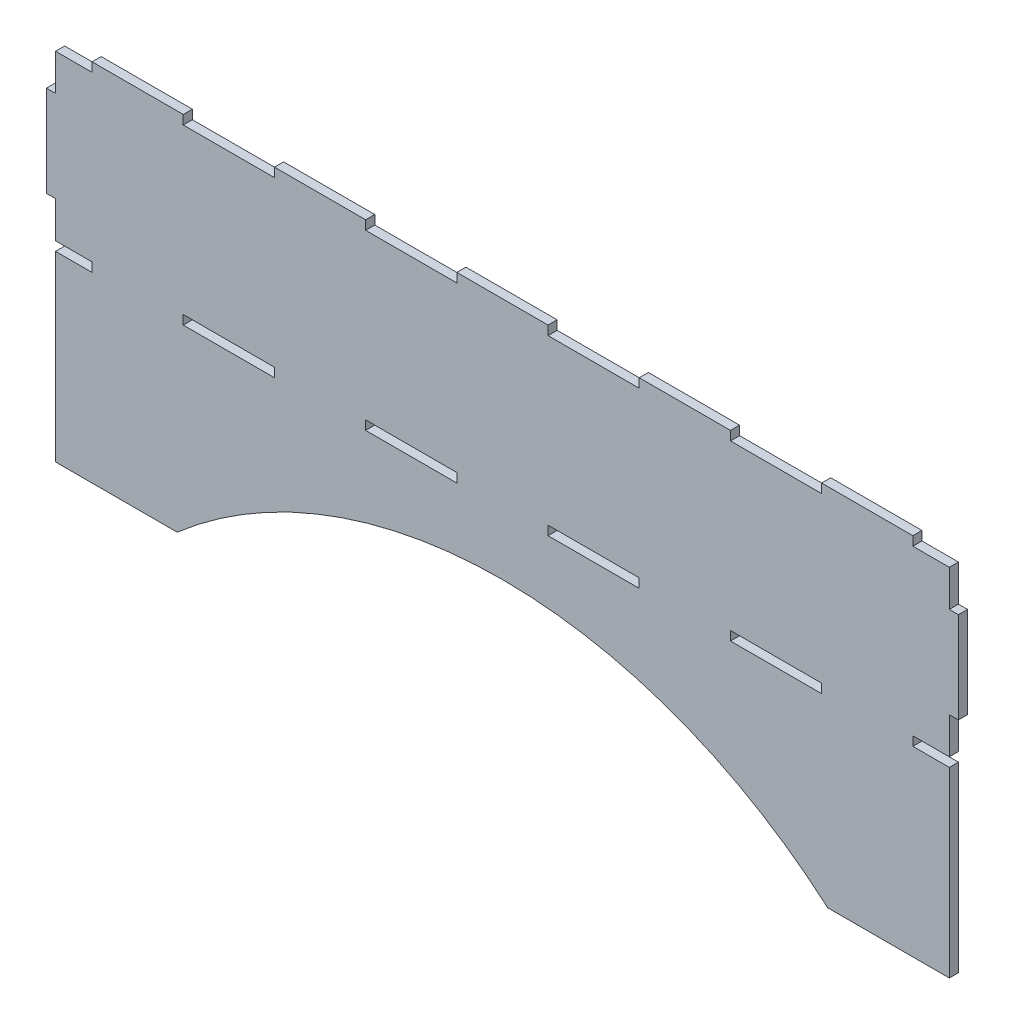
SolidWorks part; units mm, degrees
ref_plane "Front Plane" through (0, 0, 0) normal (0, 0, 1) x (1, 0, 0)
ref_plane "Top Plane" through (0, 0, 0) normal (0, 1, 0) x (1, 0, 0)
ref_plane "Right Plane" through (0, 0, 0) normal (1, 0, 0) x (0, 0, -1)
sketch "Sketch1" plane through (0, 0, 0) normal (0, 0, 1) x (1, 0, 0)
  line L1 (0, 0) -> (300, 0)
  line L2 (0, 0) -> (0, 60)
  line L3 (0, 60) -> (300, 60)
  line L4 (300, 0) -> (300, 60)
  dimension "D1" = 60
  dimension "D2" = 300
extrude "Boss-Extrude1" add sketch "Sketch1" along normal blind 3
sketch "Sketch3" plane through (0, 0, 3) normal (0, 0, 1) x (1, 0, 0)
  line L0 (0, 60) -> (0, 0) construction
  line L1 (0, 0) -> (300, 0)
  line L2 (0, 0) -> (0, -60)
  line L3 (0, -60) -> (300, -60)
  line L4 (300, 0) -> (300, -60)
extrude "Boss-Extrude2" add sketch "Sketch3" against normal blind 3
sketch "Sketch2" plane through (0, 0, 3) normal (0, 0, 1) x (1, 0, 0)
  line L0 (0, 60) -> (0, -60) construction
  line L1 (15, 0) -> (-15, 0)
  line L2 (15, 0) -> (15, 3)
  line L3 (15, 3) -> (-15, 3)
  line L4 (-15, 0) -> (-15, 3)
  line L5 (0, 60) -> (0, -60) construction
  line L6 (75, 0) -> (75, 3)
  line L7 (75, 0) -> (45, 0)
  line L8 (45, 0) -> (45, 3)
  line L9 (75, 3) -> (45, 3)
  line L10 (135, 0) -> (135, 3)
  line L11 (135, 0) -> (105, 0)
  line L12 (105, 0) -> (105, 3)
  line L13 (135, 3) -> (105, 3)
  line L14 (195, 0) -> (195, 3)
  line L15 (195, 0) -> (165, 0)
  line L16 (165, 0) -> (165, 3)
  line L17 (195, 3) -> (165, 3)
  line L18 (255, 0) -> (255, 3)
  line L19 (255, 0) -> (225, 0)
  line L20 (225, 0) -> (225, 3)
  line L21 (255, 3) -> (225, 3)
  line L22 (315, 0) -> (315, 3)
  line L23 (315, 0) -> (285, 0)
  line L24 (285, 0) -> (285, 3)
  line L25 (315, 3) -> (285, 3)
  line L26 (0, 30) -> (300, 30) construction
  line L28 (315, 57) -> (285, 57)
  line L29 (285, 60) -> (285, 57)
  line L30 (315, 60) -> (285, 60)
  line L31 (315, 60) -> (315, 57)
  line L32 (255, 57) -> (225, 57)
  line L33 (225, 60) -> (225, 57)
  line L34 (255, 60) -> (225, 60)
  line L35 (255, 60) -> (255, 57)
  line L36 (195, 57) -> (165, 57)
  line L37 (165, 60) -> (165, 57)
  line L38 (195, 60) -> (165, 60)
  line L39 (195, 60) -> (195, 57)
  line L40 (135, 57) -> (105, 57)
  line L41 (105, 60) -> (105, 57)
  line L42 (135, 60) -> (105, 60)
  line L43 (135, 60) -> (135, 57)
  line L44 (75, 57) -> (45, 57)
  line L45 (45, 60) -> (45, 57)
  line L46 (75, 60) -> (45, 60)
  line L47 (75, 60) -> (75, 57)
  line L48 (-15, 60) -> (-15, 57)
  line L49 (15, 57) -> (-15, 57)
  line L50 (15, 60) -> (15, 57)
  line L51 (15, 60) -> (-15, 60)
  line L52 (0, 60) -> (0, 45)
  line L53 (0, 15) -> (3, 15)
  line L54 (0, 15) -> (0, 0)
  line L55 (0, 0) -> (3, 0)
  line L56 (3, 15) -> (3, 0)
  line L57 (0, 60) -> (3, 60)
  line L58 (3, 60) -> (3, 45)
  line L59 (0, 45) -> (3, 45)
  line L60 (150, 60) -> (150, 0) construction
  line L61 (300, 60) -> (0, 60) construction
  line L62 (300, 0) -> (297, 0)
  line L63 (297, 15) -> (297, 0)
  line L64 (300, 15) -> (297, 15)
  line L65 (300, 15) -> (300, 0)
  line L66 (300, 60) -> (297, 60)
  line L67 (297, 60) -> (297, 45)
  line L68 (300, 45) -> (297, 45)
  line L69 (300, 60) -> (300, 45)
  dimension "D1" = 30
  dimension "D2" = 15
  dimension "D3" = 3
  dimension "D5" = 30
  dimension "D6" = 15
  dimension "D8" = 30
  dimension "D9" = 57
  dimension "D4" = 6
  dimension "D7" = 2
extrude "Cut-Extrude6" cut sketch "Sketch2" against normal blind 5
sketch "Sketch4" plane through (0, 0, 3) normal (0, 0, 1) x (1, 0, 0)
  line L0 (0, -60) -> (300, -60) construction
  line L1 (0, 0) -> (3, 0)
  line L2 (0, 0) -> (0, -60)
  line L3 (0, -60) -> (3, -60)
  line L4 (3, 0) -> (3, -60)
  line L5 (300, 0) -> (285, 0) construction
  line L6 (300, -60) -> (297, -60)
  line L7 (300, -60) -> (300, 0)
  line L8 (300, 0) -> (297, 0)
  line L9 (297, -60) -> (297, 0)
  line L10 (43, -60) -> (257, -60)
  arc A0 (43, -60) -> (257, -60) centre (150, -183.1125) cw
  point P17 (150, -20)
  dimension "D1" = 3
  dimension "D2" = 40
  dimension "D3" = 40
  dimension "D4" = 40
extrude "Cut-Extrude7" cut sketch "Sketch4" against normal blind 5
